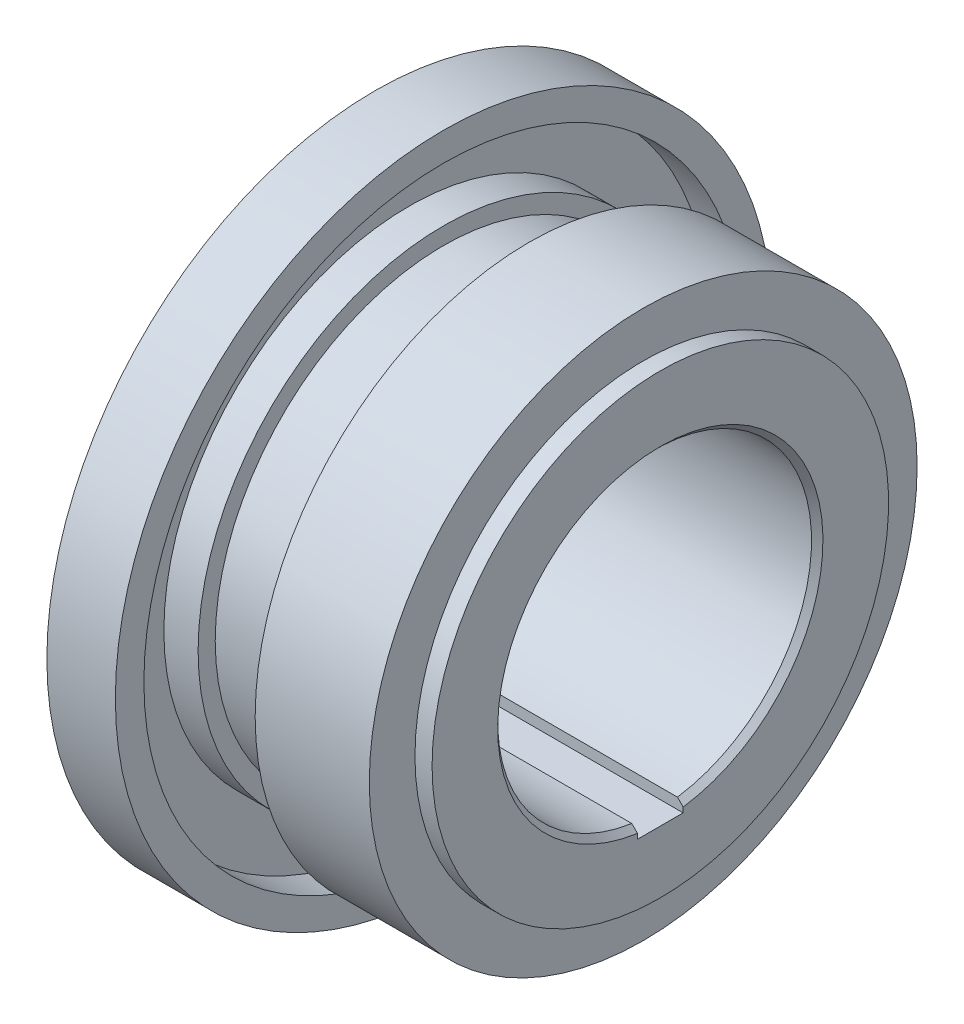
SolidWorks part; units mm, degrees
ref_plane "前视基准面" through (0, 0, 0) normal (0, 0, 1) x (1, 0, 0)
ref_plane "上视基准面" through (0, 0, 0) normal (0, 1, 0) x (1, 0, 0)
ref_plane "右视基准面" through (0, 0, 0) normal (1, 0, 0) x (0, 0, -1)
sketch "草图1" plane through (0, 0, 0) normal (0, 0, 1) x (1, 0, 0)
  line L0 (0, 0) -> (50, 0) construction
  line L1 (55, 0) -> (-55, 0) construction
  line L2 (0, 27.5) -> (0, 57.5)
  line L3 (0, -55) -> (0, 55) construction
  line L4 (0, 57.5) -> (12, 57.5)
  line L5 (12, 57.5) -> (12, 52.5)
  line L6 (12, 40) -> (50, 40)
  line L7 (0, 27.5) -> (50, 27.5)
  line L8 (50, 27.5) -> (50, 0) construction
  line L9 (0, 0) -> (0, 27.5) construction
  line L10 (50, 40) -> (50, 27.5)
  line L11 (-0.7332, 27.5) -> (0, 27.5) construction
  line L12 (12, 52.5) -> (12, 43) construction
  line L13 (12, 52.5) -> (6, 52.5)
  line L14 (12, 52.5) -> (12, 43) construction
  line L15 (12, 43) -> (6, 43)
  line L16 (6, 52.5) -> (6, 43)
  line L17 (12, 43) -> (12, 40)
  dimension "D2" = 55
  dimension "D1" = 50
  dimension "D3" = 115
  dimension "D4" = 80
  dimension "D5" = 12
  dimension "D6" = 86
  dimension "D7" = 105
  dimension "D8" = 6
revolve "旋转1" add sketch "草图1" angle 360 about L0
chamfer "倒角1" distance 1 angle 45 2 edges at (0, 0, 27.5) (50, 0, 27.5)
sketch "草图3" plane through (0, 0, 0) normal (0, 0, 1) x (1, 0, 0)
  line L0 (27.5, 0) -> (-27.5, 0) construction
  line L1 (27, 0) -> (47, 0) construction
  line L2 (27, 39.9883) -> (27, 48)
  line L3 (27, 48) -> (47, 48)
  line L4 (47, 39.9883) -> (47, 48)
  line L5 (0, -63.25) -> (0, 63.25) construction
  line L6 (27, 39.9883) -> (47, 39.9883)
  line L7 (47, 0) -> (47, 39.9883) construction
  line L8 (27, 0) -> (27, 39.9883) construction
  point P6 (37, 48)
  dimension "D1" = 96
  dimension "D2" = 20
  dimension "D3" = 37
revolve "旋转2" add sketch "草图3" angle 360 about L1
sketch "草图4" plane through (0, 0, 0) normal (-1, 0, 0) x (0, 0, 1)
  line L0 (0, -27.5) -> (0, 27.5) construction
  line L1 (-4, -29.1) -> (4, -29.1)
  line L2 (-4, -29.1) -> (-4, -22.1122)
  line L3 (-4, -22.1122) -> (4, -22.1122)
  line L4 (4, -29.1) -> (4, -22.1122)
  line L5 (-4, -29.1) -> (4, -22.1122) construction
  line L6 (-4, -22.1122) -> (4, -29.1) construction
  circle A20 centre (0, 0) radius 28.5 construction
  point P0 (0, -25.6061)
  dimension "D2" = 57.6
  dimension "D1" = 8
extrude "切除-拉伸1" cut sketch "草图4" against normal through all
